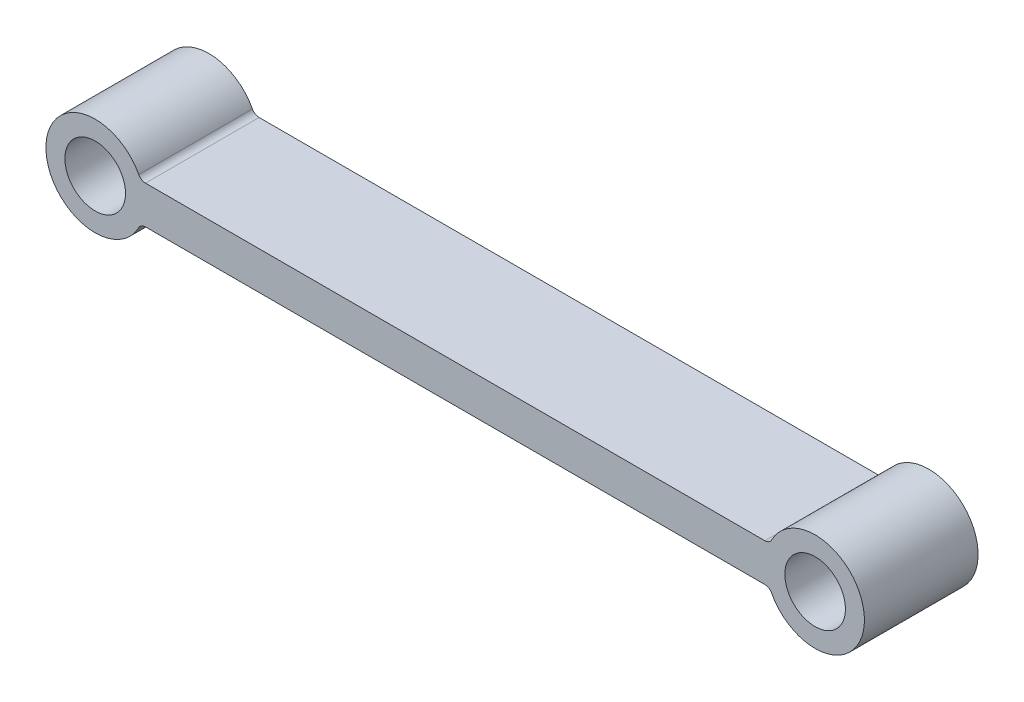
SolidWorks part; units mm, degrees
ref_plane "Front Plane" through (0, 0, 0) normal (0, 0, 1) x (1, 0, 0)
ref_plane "Top Plane" through (0, 0, 0) normal (0, 1, 0) x (1, 0, 0)
ref_plane "Right Plane" through (0, 0, 0) normal (1, 0, 0) x (0, 0, -1)
sketch "Sketch1" plane through (0, 0, 0) normal (0, 0, 1) x (1, 0, 0)
  line L0 (0, -17.9006) -> (0, -4.1871) construction
  line L1 (-40.8668, 2.5) -> (40.8668, 2.5)
  line L2 (-39.586, 0) -> (-16.1769, 0) construction
  line L3 (-40.8668, -2.5) -> (40.8668, -2.5)
  circle A0 centre (-47.5, 0) radius 4
  circle A4 centre (47.5, 0) radius 4
  arc A5 (-41.7512, 3.0333) -> (-41.7512, -3.0333) centre (-47.5, 0) ccw
  arc A6 (-41.7512, 3.0333) -> (-40.8668, 2.5) centre (-40.8668, 3.5) ccw
  arc A7 (-41.7512, -3.0333) -> (-40.8668, -2.5) centre (-40.8668, -3.5) cw
  arc A8 (41.7512, -3.0333) -> (40.8668, -2.5) centre (40.8668, -3.5) ccw
  arc A9 (41.7512, 3.0333) -> (41.7512, -3.0333) centre (47.5, 0) cw
  arc A10 (41.7512, 3.0333) -> (40.8668, 2.5) centre (40.8668, 3.5) cw
  point P0 (0, 0)
  point P3 (-30.6564, 3.3362)
  point P6 (0, 2.5)
  point P8 (0, 0)
  point P9 (0, 0)
  point P16 (0, -2)
  point P18 (0, 2)
  point P20 (0, 0)
  point P21 (0, 0)
  point P31 (0, -2.5)
  dimension "D1" = 8
  dimension "D4" = 1
  dimension "D2" = 5
  dimension "D3" = 2.5
  dimension "D5" = 95
extrude "Boss-Extrude1" add sketch "Sketch1" along normal blind 15
equation "\"bonethickness\"= 5"
equation "\"bone_bore_extension\"= \"bonethickness\" / 2"
equation "\"D2@Sketch1\"=\"bonethickness\""
equation "\"D3@Sketch1\"=\"bone_bore_extension\""
